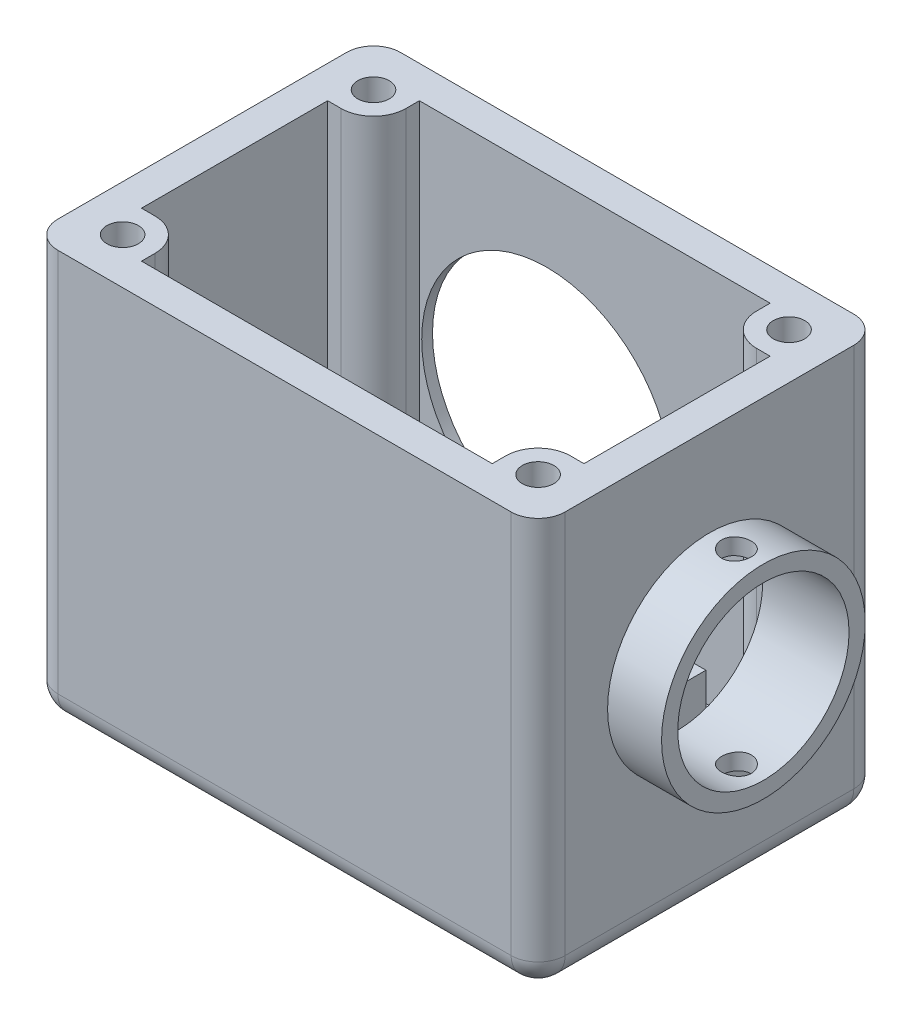
SolidWorks part; units mm, degrees
other "Markup1"
sketch "Sketch54" plane through (-29.5417, 76.2, -31.75) normal (-0.3541, 0.9345, -0.0352) x (0.0745, -0.0093, -0.9972)
ref_plane "Front Plane" through (0, 0, 0) normal (0, 0, 1) x (1, 0, 0)
ref_plane "Top Plane" through (0, 0, 0) normal (0, 1, 0) x (1, 0, 0)
ref_plane "Right Plane" through (0, 0, 0) normal (1, 0, 0) x (0, 0, -1)
sketch "Sketch1" plane through (0, 0, 0) normal (0, 1, 0) x (1, 0, 0)
  line L1 (0, 31.75) -> (94, 31.75)
  line L2 (0, 31.75) -> (0, -31.75)
  line L3 (0, -31.75) -> (94, -31.75)
  line L4 (94, 31.75) -> (94, -31.75)
  point P4 (0, 0)
extrude "Boss-Extrude1" add sketch "Sketch1" along normal blind 76.2
sketch "Sketch2" plane through (0, 76.2, 0) normal (0, 1, 0) x (1, 0, 0)
  line L0 (0, 31.75) -> (0, -31.75) construction
  line L1 (6, 25.75) -> (88, 25.75)
  line L2 (6, 25.75) -> (6, -25.75)
  line L3 (6, -25.75) -> (88, -25.75)
  line L4 (88, 25.75) -> (88, -25.75)
  line L5 (94, 31.75) -> (0, 31.75) construction
  line L6 (0, -31.75) -> (94, -31.75) construction
  line L7 (94, -31.75) -> (94, 31.75) construction
  dimension "D1" = 6
  dimension "D2" = 6
  dimension "D3" = 6
  dimension "D4" = 6
extrude "Cut-Extrude1" cut sketch "Sketch2" against normal blind 70.2
sketch "Sketch3" plane through (0, 0, 31.75) normal (0, 0, 1) x (1, 0, 0)
  line L0 (340.2875, 38.1) -> (-29.5417, 38.1) construction
  line L1 (94, 76.2) -> (94, 0) construction
  circle A1 centre (55.9, 38.1) radius 31.95
  dimension "D1" = 38.1
sketch "Sketch7" plane through (0, 0, -31.75) normal (0, 0, -1) x (-1, 0, 0)
  line L0 (-340.2875, 38.1) -> (29.5417, 38.1) construction
  line L1 (0, 76.2) -> (0, 0) construction
  circle A0 centre (-38.1, 38.1) radius 33
  dimension "D1" = 38.1
extrude "Cut-Extrude4" cut sketch "Sketch7" against normal blind 4
sketch "Sketch8" plane through (0, 0, -25.75) normal (0, 0, 1) x (1, 0, 0)
  line L0 (340.2875, 38.1) -> (-29.5417, 38.1) construction
  line L1 (0, 76.2) -> (0, 0) construction
  circle A0 centre (38.1, 38.1) radius 12.55
  dimension "D1" = 38.1
extrude "Cut-Extrude5" cut sketch "Sketch8" against normal blind 2
sketch "Sketch11" plane through (0, 0, 25.75) normal (0, 0, -1) x (-1, 0, 0)
  line L1 (-66, 48.2) -> (-25.5, 48.2) construction
  line L2 (-66, 48.2) -> (-66, 28) construction
  line L3 (-66, 28) -> (-25.5, 28) construction
  line L4 (-25.5, 48.2) -> (-25.5, 28) construction
  dimension "D1" = 10.1
  dimension "D2" = 20.2
  dimension "D3" = 10.1
  dimension "D4" = 40.5
ref_plane "Plane2" through (0, 28, 0) normal (0, 1, 0) x (1, 0, 0)
sketch "Sketch15" plane through (0, 28, 0) normal (0, 1, 0) x (1, 0, 0)
  line L15 (88, 25.75) -> (6, 25.75) construction
  line L17 (12.25, 9.1) -> (84.25, 9.1)
  line L18 (12.25, 9.1) -> (12.25, -15.9)
  line L19 (12.25, -15.9) -> (84.25, -15.9)
  line L20 (84.25, 9.1) -> (84.25, -15.9)
  line L22 (38.1, 27.75) -> (38.1, -17.0385) construction
  line L23 (50.65, 27.75) -> (25.55, 27.75) construction
  line L24 (48.25, 9.1) -> (48.25, -15.9) construction
  line L25 (15.75, 5.1) -> (15.75, -6.3781) construction
  dimension "D1" = 16.65
  dimension "D2" = 25.85
  dimension "D3" = 72
  dimension "D4" = 25
  dimension "D6" = 4
  dimension "D7" = 3.5
extrude "Boss-Extrude3" add sketch "Sketch15" against normal blind 22
sketch3d "3DSketch2"
  line L0 (6, 6, 0) -> (344.0999, 6, 0) construction
  line L1 (6, 6, -25.75) -> (6, 6, 25.75) construction
ref_plane "Plane3" through (0, 0, 0) normal (0, 0, 1) x (1, 0, 0)
fillet "Fillet1" radius 5 8 edges at (0, 0, 0) (47, 0, 31.75) (0, 38.1, 31.75) (0, 38.1, -31.75) (47, 0, -31.75) (94, 0, 0) (94, 38.1, 31.75) (94, 38.1, -31.75)
sketch "Sketch44" plane through (0, 76.2, 0) normal (0, 1, 0) x (1, 0, 0)
  line L0 (8.5, 33.9856) -> (8.5, -37.2084) construction
  line L1 (-4.0359, -23.25) -> (97.4564, -23.25) construction
  line L2 (-4.0359, 23.25) -> (97.4564, 23.25) construction
  line L3 (85.5, -34.1183) -> (85.5, 34.8738) construction
  line L4 (6, 25.75) -> (6, -25.75) construction
  line L5 (88, -25.75) -> (88, 25.75) construction
  line L6 (88, 25.75) -> (6, 25.75) construction
  line L7 (6, -25.75) -> (88, -25.75) construction
  line L8 (8.5, 17.25) -> (6, 17.25)
  line L10 (14.5, 23.25) -> (14.5, 25.75)
  line L11 (88, 25.75) -> (6, 25.75) construction
  line L12 (6, 25.75) -> (6, -25.75) construction
  line L13 (6, 17.25) -> (6, 25.75)
  line L14 (6, 25.75) -> (14.5, 25.75)
  line L15 (8.5, -17.25) -> (6, -17.25)
  line L16 (6, -17.25) -> (6, -25.75)
  line L17 (6, -25.75) -> (14.5, -25.75)
  line L18 (14.5, -25.75) -> (14.5, -23.25)
  line L19 (79.5, -23.25) -> (79.5, -25.75)
  line L20 (79.5, -25.75) -> (88, -25.75)
  line L21 (88, -25.75) -> (88, -17.25)
  line L22 (88, -17.25) -> (85.5, -17.25)
  line L23 (79.5, 23.25) -> (79.5, 25.75)
  line L24 (79.5, 25.75) -> (88, 25.75)
  line L25 (88, 25.75) -> (88, 17.25)
  line L26 (88, 17.25) -> (85.5, 17.25)
  arc A0 (8.5, 17.25) -> (14.5, 23.25) centre (8.5, 23.25) ccw
  arc A1 (14.5, -23.25) -> (8.5, -17.25) centre (8.5, -23.25) ccw
  arc A2 (85.5, -17.25) -> (79.5, -23.25) centre (85.5, -23.25) ccw
  arc A3 (79.5, 23.25) -> (85.5, 17.25) centre (85.5, 23.25) ccw
  dimension "D1" = 2.5
  dimension "D2" = 2.5
  dimension "D3" = 2.5
  dimension "D4" = 2.5
extrude "Boss-Extrude4" add sketch "Sketch44" against normal up to surface (70.2 mm away) up to face at (48.25, 6, 3.4)
sketch "Sketch45" plane through (0, 76.2, 0) normal (0, 1, 0) x (1, 0, 0)
  line L0 (-5.0131, 0) -> (101.0279, 0) construction
  circle A0 centre (8.5, 23.25) radius 3.4
  circle A1 centre (85.5, 23.25) radius 3.4
  circle A2 centre (85.5, -23.25) radius 3.4
  circle A3 centre (8.5, -23.25) radius 3.4
hole_wizard "Ø1.0mm Dowel Hole2" positions "Sketch48" profile "Sketch47" hole size "Ø1.0" standard "ANSI Metric"
sketch "Sketch48" plane through (0, 76.2, 0) normal (0, 1, 0) x (1, 0, 0)
  point P0 (8.5, 23.25)
  point P4 (8.5, -23.25)
  point P7 (85.5, -23.25)
  point P10 (85.5, 23.25)
sketch "Sketch47" plane through (8.5, 76.2, -23.25) normal (1, 0, 0) x (0, 0, 1)
  line L0 (0, 0) -> (0, 12.5075)
  line L1 (0, 12.5075) -> (2.925, 10.75)
  line L2 (2.925, 10.75) -> (2.925, 0)
  line L5 (2.925, 0) -> (0, 0)
  line L10 (0, 12.5075) -> (-2.925, 10.75) construction
  line L11 (0, -6.35) -> (0, 107.95) construction
  dimension "Hole Dia." = 5.85
  dimension "Hole Depth" = 10.75
  dimension "Drill Angle" = 118
sketch "Sketch49" plane through (94, 0, 0) normal (1, 0, 0) x (0, 0, -1)
  line L0 (0, 76.2) -> (0, -3.4439) construction
  line L1 (-26.75, 76.2) -> (26.75, 76.2) construction
  line L2 (-35.746, 40.6) -> (38.1435, 40.6) construction
  circle A0 centre (0, 40.6) radius 15.875
extrude "Cut-Extrude7" cut sketch "Sketch49" against normal up to surface (6 mm away) up to face at (88, 41.1, 0)
sketch "Sketch51" plane through (94, 0, 0) normal (1, 0, 0) x (0, 0, -1)
  circle A0 centre (0, 40.6) radius 15.875
  circle A1 centre (0, 40.6) radius 18.875
extrude "Boss-Extrude5" add sketch "Sketch51" along normal blind 10
ref_plane "Plane4" through (0, 59.475, 0) normal (0, 1, 0) x (-1, 0, 0)
sketch "Sketch52" plane through (0, 59.475, 0) normal (0, 1, 0) x (-1, 0, 0)
  line L0 (-104, 0) -> (-91.3804, 0) construction
  line L1 (-104, 18.875) -> (-104, -18.875) construction
  line L2 (-88, -5.5815) -> (-88, 5.2767) construction
  line L3 (-88, 17.25) -> (-88, -17.25) construction
  line L4 (-88, 17.25) -> (-88, -17.25) construction
  circle A0 centre (-99, 0) radius 2.75
  dimension "D1" = 5
  dimension "D2" = 11
extrude "Cut-Extrude8" cut sketch "Sketch52" against normal through all
sketch "Sketch53" plane through (0, 0, -27.75) normal (0, 0, -1) x (-1, 0, 0)
  arc A0 (-38.1, 14.93) -> (-38.1, 61.27) centre (-38.1, 38.1) ccw construction
  circle A1 centre (-38.1, 38.1) radius 23.17
extrude "Cut-Extrude9" cut sketch "Sketch53" against normal up to surface (2 mm away) up to face at (50.65, 38.1, -25.75)
fillet "Fillet2" [suppressed] radius 3
fillet "Fillet3" [suppressed] radius 2
sketch "Sketch55" plane through (0, 28, 0) normal (0, 1, 0) x (1, 0, 0)
  line L0 (38.1, 27.75) -> (38.1, -21.5983) construction
  line L1 (71.1, 27.75) -> (5.1, 27.75) construction
  line L2 (15.75, 6.865) -> (15.75, -8.6282) construction
  line L3 (12.25, 9.1) -> (12.25, -15.9) construction
  line L4 (84.25, 9.1) -> (12.25, 9.1) construction
  line L5 (48.25, 9.1) -> (48.25, -15.9) construction
  line L6 (12.25, -15.9) -> (84.25, -15.9) construction
  circle A0 centre (15.75, 5.1) radius 2
  circle A1 centre (15.75, -2.9) radius 2
  circle A2 centre (80.75, -2.9) radius 2
  circle A3 centre (80.75, 5.1) radius 2
  dimension "D2" = 4
  dimension "D1" = 3.5
  dimension "D3" = 12
hole_wizard "Bracket Holes" positions "Sketch56" profile "Sketch57" hole size "Ø1.0" standard "ANSI Metric"
sketch "Sketch56" plane through (0, 28, 0) normal (0, 1, 0) x (1, 0, 0)
  point P0 (15.75, 5.1)
  point P3 (15.75, -2.9)
  point P6 (80.75, -2.9)
  point P9 (80.75, 5.1)
sketch "Sketch57" plane through (15.75, 28, -5.1) normal (1, 0, 0) x (0, 0, 1)
  line L0 (0, 0) -> (0, 11.9517)
  line L1 (0, 11.9517) -> (2, 10.75)
  line L2 (2, 10.75) -> (2, 0)
  line L5 (2, 0) -> (0, 0)
  line L10 (0, 11.9517) -> (-2, 10.75) construction
  line L11 (0, -6.35) -> (0, 107.95) construction
  dimension "Hole Dia." = 4
  dimension "Hole Depth" = 10.75
  dimension "Drill Angle" = 118
